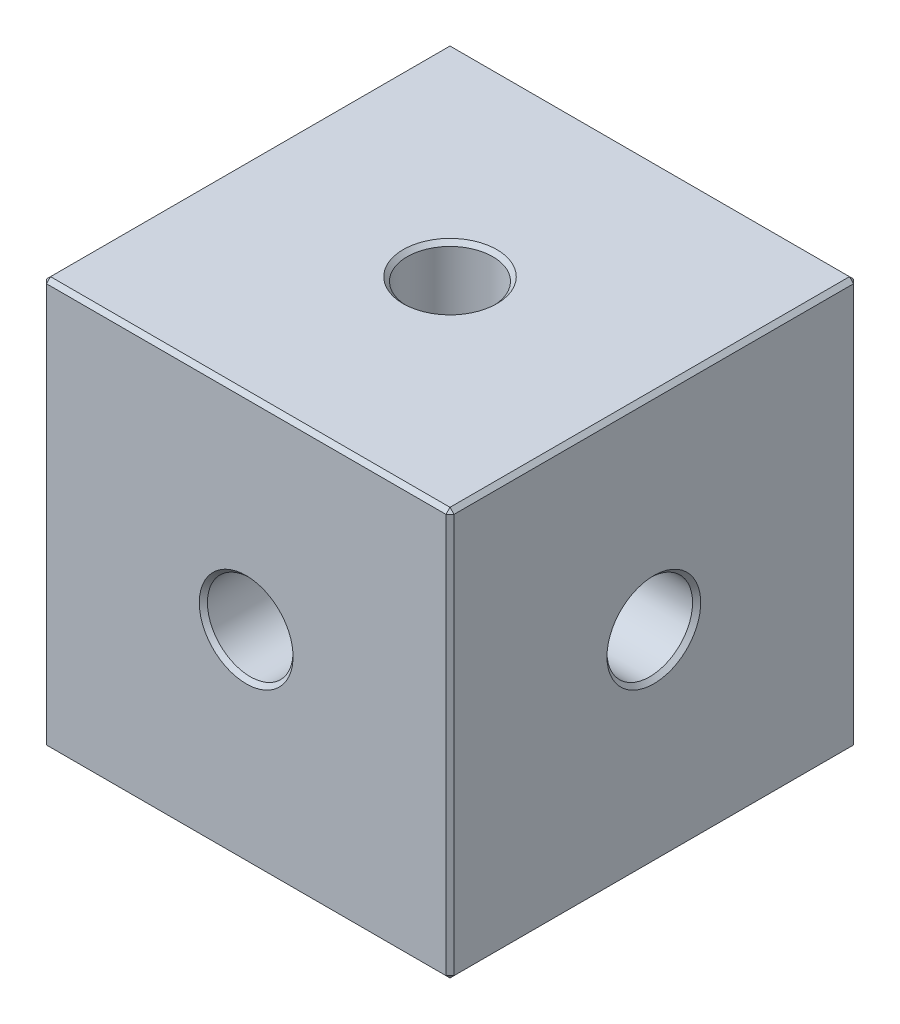
SolidWorks part; units mm, degrees
ref_plane "前视基准面" through (0, 0, 0) normal (0, 0, 1) x (1, 0, 0)
ref_plane "上视基准面" through (0, 0, 0) normal (0, 1, 0) x (1, 0, 0)
ref_plane "右视基准面" through (0, 0, 0) normal (1, 0, 0) x (0, 0, -1)
sketch "草图1" plane through (0, 0, 0) normal (0, 1, 0) x (1, 0, 0)
  line L1 (-10, 10) -> (10, 10)
  line L2 (-10, 10) -> (-10, -10)
  line L3 (-10, -10) -> (10, -10)
  line L4 (10, 10) -> (10, -10)
  line L5 (-10, 10) -> (10, -10) construction
  line L6 (-10, -10) -> (10, 10) construction
  point P0 (0, 0)
  dimension "D1" = 20
extrude "凸台-拉伸1" add sketch "草图1" along normal mid plane 20
hole_wizard "M5 螺纹孔1" positions "草图2" profile "草图3" tap size "M5" standard "GB" end condition through all
sketch "草图2" plane through (0, 0, 10) normal (0, 0, 1) x (1, 0, 0)
  point P0 (0, 0)
sketch "草图3" plane through (0, 0, 10) normal (1, 0, 0) x (0, -1, 0)
  line L0 (0, 0) -> (0, 20)
  line L1 (0, 20) -> (2.1, 20)
  line L2 (2.1, 20) -> (2.1, 0)
  line L5 (2.1, 0) -> (0, 0)
  line L11 (0, -6.35) -> (0, 107.95) construction
  dimension "通孔螺纹孔钻头直径" = 4.2
  dimension "通孔螺纹孔钻头深度" = 20
cosmetic thread "孔螺蚊线1" parameters "D2"=5
hole_wizard "M5 螺纹孔2" positions "草图4" profile "草图5" tap size "M5" standard "GB" end condition through all
sketch "草图4" plane through (0, 10, 0) normal (0, 1, 0) x (1, 0, 0)
  point P0 (0, 0)
sketch "草图5" plane through (0, 10, 0) normal (1, 0, 0) x (0, 0, 1)
  line L0 (0, 0) -> (0, 20)
  line L1 (0, 20) -> (2.1, 20)
  line L2 (2.1, 20) -> (2.1, 0)
  line L5 (2.1, 0) -> (0, 0)
  line L11 (0, -6.35) -> (0, 107.95) construction
  dimension "通孔螺纹孔钻头直径" = 4.2
  dimension "通孔螺纹孔钻头深度" = 20
cosmetic thread "孔螺蚊线2" parameters "D2"=5
hole_wizard "M5 螺纹孔3" positions "草图6" profile "草图7" tap size "M5" standard "GB" end condition through all
sketch "草图6" plane through (10, 0, 0) normal (1, 0, 0) x (0, 0, -1)
  point P0 (0, 0)
sketch "草图7" plane through (10, 0, 0) normal (0, 1, 0) x (0, 0, -1)
  line L0 (0, 0) -> (0, 20)
  line L1 (0, 20) -> (2.1, 20)
  line L2 (2.1, 20) -> (2.1, 0)
  line L5 (2.1, 0) -> (0, 0)
  line L11 (0, -6.35) -> (0, 107.95) construction
  dimension "通孔螺纹孔钻头直径" = 4.2
  dimension "通孔螺纹孔钻头深度" = 20
cosmetic thread "孔螺蚊线3" parameters "D2"=5
chamfer "倒角1" distance 0.2 angle 45 18 edges at (0, -10, 2.1) (-10, 0, -2.1) (2.1, 0, -10) (10, 0, -2.1) (2.1, 0, 10) (-10, -10, 0) (-10, 0, -10) (0, -10, -10) (10, 0, -10) (10, -10, 0) (-10, 0, 10) (0, -10, 10) (10, 0, 10) (0, 10, 10) (-10, 10, 0) (0, 10, -10) (10, 10, 0) (0, 10, 2.1)
